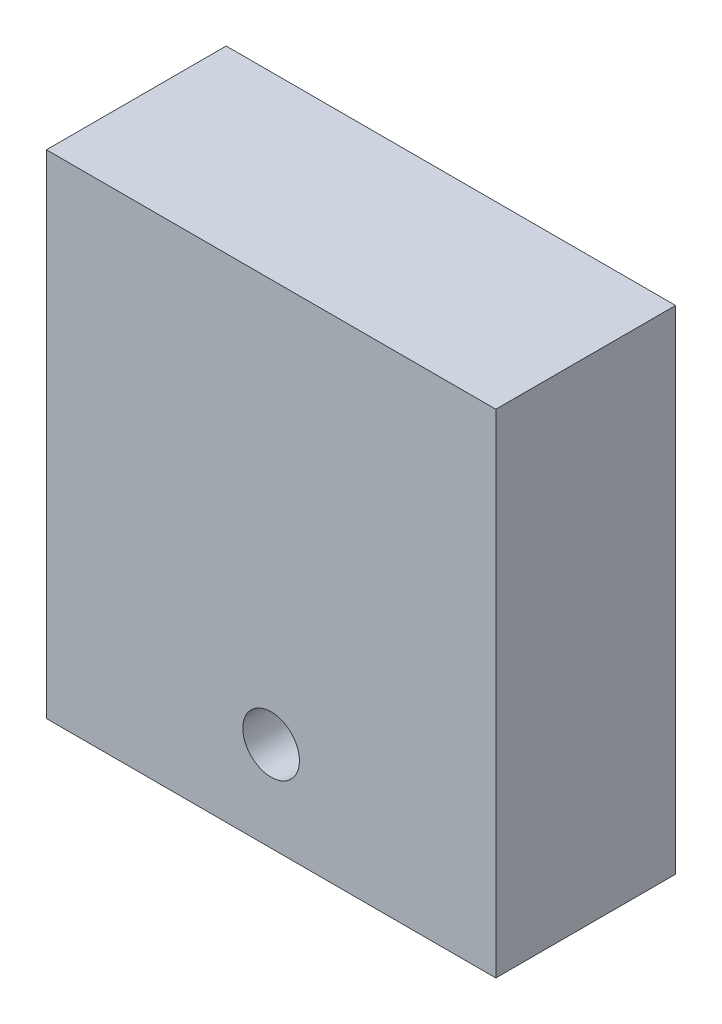
SolidWorks part; units mm, degrees
material "Balsa"
ref_plane "Front Plane" through (0, 0, 0) normal (0, 0, 1) x (1, 0, 0)
ref_plane "Top Plane" through (0, 0, 0) normal (0, 1, 0) x (1, 0, 0)
ref_plane "Right Plane" through (0, 0, 0) normal (1, 0, 0) x (0, 0, -1)
sketch "Sketch1" plane through (0, 0, 0) normal (0, 0, 1) x (1, 0, 0)
  line L1 (0, 0) -> (15.875, 0)
  line L2 (0, 0) -> (0, 17.4)
  line L3 (0, 17.4) -> (15.875, 17.4)
  line L4 (15.875, 0) -> (15.875, 17.4)
  dimension "D1" = 15.875
  dimension "D2" = 17.4
extrude "Boss-Extrude1" add sketch "Sketch1" along normal blind 6.35
sketch "Sketch2" plane through (0, 0, 6.35) normal (0, 0, 1) x (1, 0, 0)
  line L0 (7.9375, 3.175) -> (0, 3.175) construction
  line L2 (7.9375, 3.175) -> (7.9375, 17.4) construction
  line L3 (15.875, 17.4) -> (0, 17.4) construction
  line L4 (0, 0) -> (15.875, 0) construction
  circle A0 centre (7.9375, 3.175) radius 1
  dimension "D1" = 2
  dimension "D2" = 3.175
extrude "Cut-Extrude1" cut sketch "Sketch2" against normal through all
